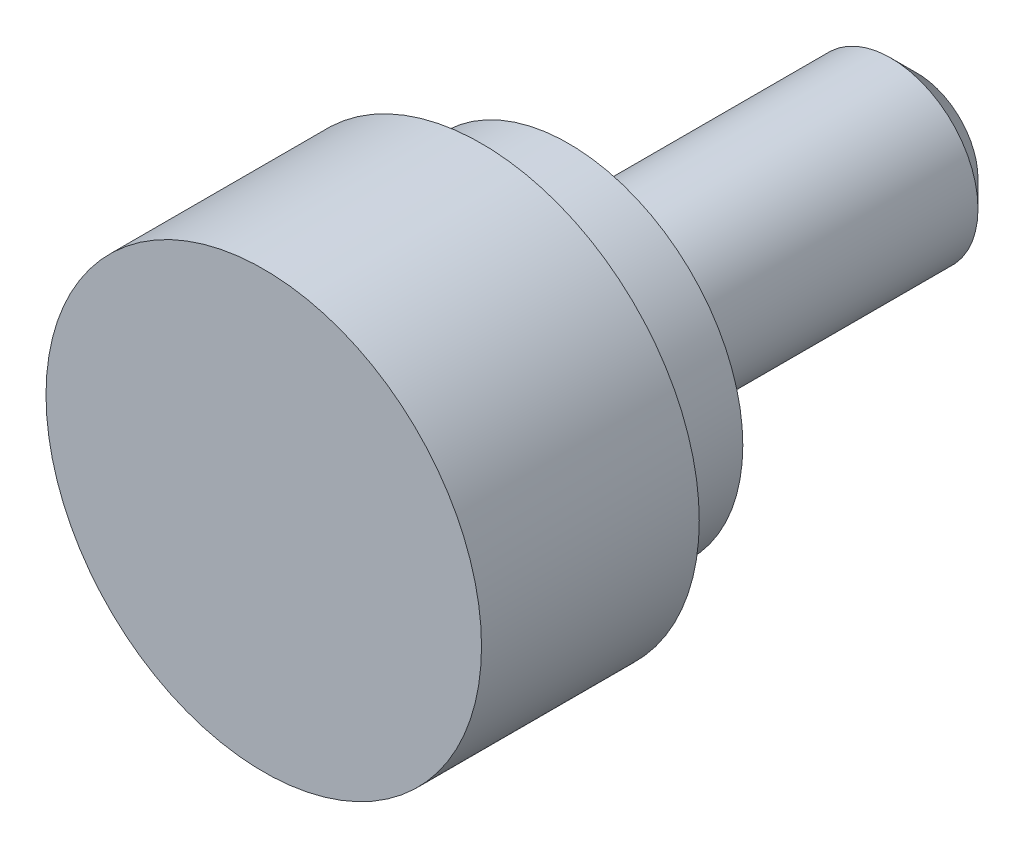
SolidWorks part; units mm, degrees
material "Brass"
ref_plane "Front" through (0, 0, 0) normal (0, 0, 1) x (1, 0, 0)
ref_plane "Top" through (0, 0, 0) normal (0, 1, 0) x (1, 0, 0)
ref_plane "Right" through (0, 0, 0) normal (1, 0, 0) x (0, 0, -1)
sketch "Sketch20" plane through (0, 0, 0) normal (1, 0, 0) x (0, 0, -1)
  line L0 (0, 0) -> (12.7, 0) construction
  line L1 (12.7, 3.175) -> (12.7, -3.175) construction
  line L2 (-3.175, 7.9375) -> (-3.175, -7.9375) construction
  line L3 (-11.1125, 7.9375) -> (-11.1125, -7.9375) construction
  line L4 (0, 6.35) -> (0, -6.35) construction
  point P9 (6.985, -3.175)
  point P11 (-3.175, 0)
  point P14 (0, 0)
  dimension "D1" = 6.35
  dimension "D2" = 12.7
  dimension "D3" = 5.715
  dimension "Shoulder Diameter" = 12.7
  dimension "Shoulder Length" = 3.175
  dimension "Head Diameter" = 15.875
  dimension "Head Height" = 7.9375
sketch "Sketch1" plane through (0, 0, 0) normal (0, 0, 1) x (1, 0, 0)
  circle A0 centre (0, 0) radius 3.175
  dimension "dia" = 6.35
extrude "Extrude1" add sketch "Sketch1" against normal blind 12.7
chamfer "Chamfer2" distance 0.9525 angle 45 1 edges at (3.175, 0, -12.7)
sketch "Sketch27" plane through (0, 0, 0) normal (0, 0, 1) x (1, 0, 0)
  circle A0 centre (0, 0) radius 6.35
extrude "Boss-Extrude4" add sketch "Sketch27" along normal up to vertex (3.175 mm away) up to point (0, 0, 3.175)
sketch "Sketch21" plane through (0, 0, 3.175) normal (0, 0, 1) x (1, 0, 0)
  line L0 (-7.9375, 0) -> (7.9375, 0) construction
  circle A0 centre (0, 0) radius 7.9375
extrude "Boss-Extrude1" add sketch "Sketch21" along normal up to vertex (7.9375 mm away) up to point (0, -7.9375, 11.1125)
equation "\"D1@Sketch20\" = \"dia@Sketch1\""
equation "\"D2@Sketch20\" = \"Lg@Extrude1\""
